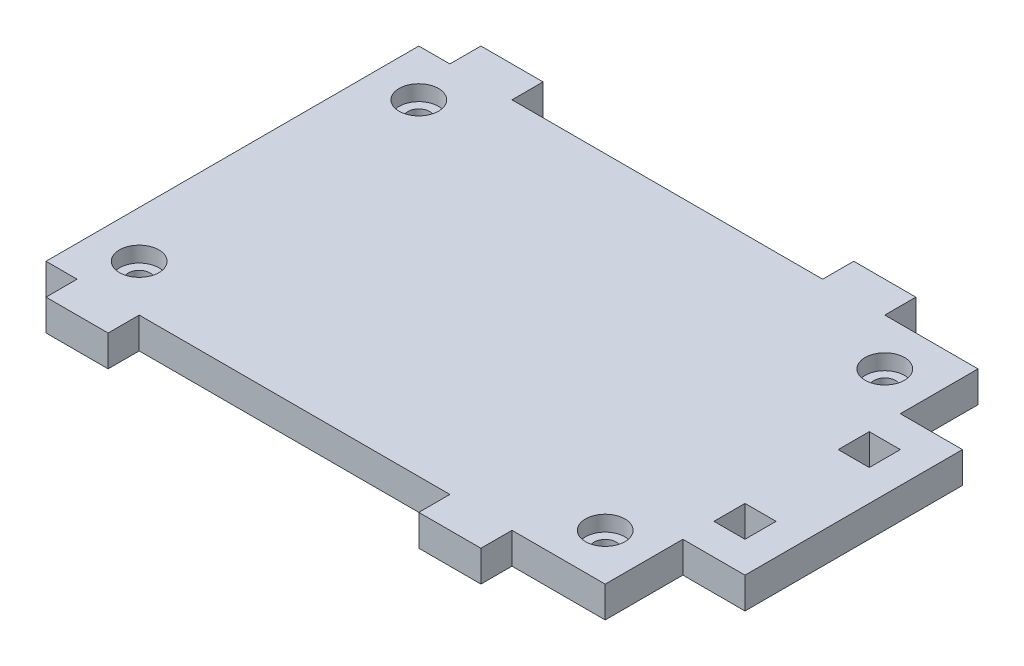
SolidWorks part; units mm, degrees
ref_plane "Front Plane" through (0, 0, 0) normal (0, 0, 1) x (1, 0, 0)
ref_plane "Top Plane" through (0, 0, 0) normal (0, 1, 0) x (1, 0, 0)
ref_plane "Right Plane" through (0, 0, 0) normal (1, 0, 0) x (0, 0, -1)
sketch "Sketch1" plane through (0, 0, 0) normal (0, 1, 0) x (1, 0, 0)
  line L0 (30, 30) -> (45, 30)
  line L1 (-45, -30) -> (-40, -30)
  line L2 (-45, -30) -> (-45, 30)
  line L3 (-45, 30) -> (-40, 30)
  line L4 (45, -30) -> (45, -17.5)
  line L5 (-45, -30) -> (45, 30) construction
  line L6 (-45, 30) -> (45, -30) construction
  line L8 (30, 30) -> (30, 35)
  line L9 (30, 35) -> (20, 35)
  line L10 (20, 30) -> (20, 35)
  line L12 (30, -30) -> (30, -35)
  line L13 (30, -35) -> (20, -35)
  line L14 (20, -30) -> (20, -35)
  line L16 (-30, 30) -> (-30, 35)
  line L17 (-30, 35) -> (-40, 35)
  line L18 (-40, 30) -> (-40, 35)
  line L20 (-30, -30) -> (-30, -35)
  line L21 (-30, -35) -> (-40, -35)
  line L22 (-40, -30) -> (-40, -35)
  line L27 (-30, 30) -> (20, 30)
  line L28 (-30, -30) -> (20, -30)
  line L29 (30, -30) -> (45, -30)
  line L31 (45, -17.5) -> (55, -17.5)
  line L33 (45, 17.5) -> (55, 17.5)
  line L34 (55, -17.5) -> (55, 17.5)
  line L44 (45, 17.5) -> (45, 30)
  line L46 (45, 12.5) -> (50, 12.5)
  line L52 (45, 12.5) -> (45, 7.5)
  line L53 (45, 7.5) -> (50, 7.5)
  line L54 (50, 12.5) -> (50, 7.5)
  line L55 (45, -7.5) -> (50, -7.5)
  line L56 (45, -7.5) -> (45, -12.5)
  line L57 (45, -12.5) -> (50, -12.5)
  line L58 (50, -7.5) -> (50, -12.5)
  circle A0 centre (37.5, 22.5) radius 1.75
  circle A1 centre (37.5, -22.5) radius 1.75
  circle A2 centre (-37.5, 22.5) radius 1.75
  circle A3 centre (-37.5, -22.5) radius 1.75
  point P0 (0, 0)
  dimension "D13" = 3.5
  dimension "D14" = 3.5
  dimension "D15" = 3.5
  dimension "D16" = 3.5
  dimension "D1" = 90
  dimension "D2" = 60
  dimension "D3" = 5
  dimension "D4" = 15
  dimension "D5" = 10
  dimension "D6" = 5
  dimension "D7" = 50
  dimension "D8" = 10
  dimension "D9" = 45
  dimension "D10" = 7.5
  dimension "D11" = 7.5
  dimension "D12" = 75
  dimension "D17" = 10
  dimension "D18" = 12.5
  dimension "D19" = 12.5
  dimension "D20" = 5
  dimension "D21" = 5
  dimension "D22" = 5
  dimension "D23" = 10
  dimension "D24" = 5
  dimension "D25" = 5
  dimension "D26" = 15
  dimension "D27" = 10
extrude "Boss-Extrude1" add sketch "Sketch1" along normal blind 5
sketch "Sketch2" plane through (0, 5, 0) normal (0, 1, 0) x (1, 0, 0)
  circle A0 centre (-37.5, 22.5) radius 3.175
  circle A1 centre (-37.5, -22.5) radius 3.175
  circle A2 centre (37.5, 22.5) radius 3.175
  circle A3 centre (37.5, -22.5) radius 3.175
extrude "Cut-Extrude1" cut sketch "Sketch2" against normal blind 2.5
